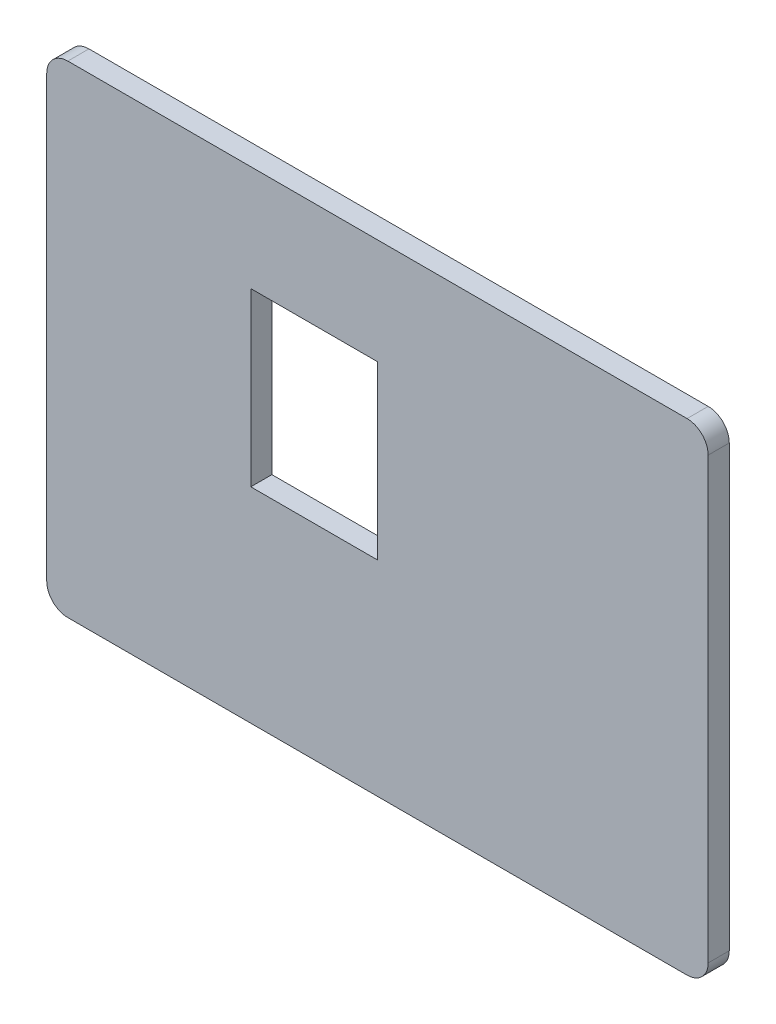
SolidWorks part; units mm, degrees
ref_plane "Alzado" through (0, 0, 0) normal (0, 0, 1) x (1, 0, 0)
ref_plane "Planta" through (0, 0, 0) normal (0, 1, 0) x (1, 0, 0)
ref_plane "Vista lateral" through (0, 0, 0) normal (1, 0, 0) x (0, 0, -1)
sketch "Croquis1" plane through (0, 0, 0) normal (0, 0, 1) x (1, 0, 0)
  line L1 (-25.0652, 6.8383) -> (21.9348, 6.8383)
  line L2 (-25.0652, 6.8383) -> (-25.0652, -27.4117)
  line L3 (-25.0652, -27.4117) -> (21.9348, -27.4117)
  line L4 (21.9348, 6.8383) -> (21.9348, -27.4117)
  dimension "D1" = 47
  dimension "D2" = 34.25
extrude "Saliente-Extruir1" add sketch "Croquis1" along normal blind 1.5
sketch "Croquis2" plane through (0, 0, 0) normal (0, 0, 1) x (1, 0, 0)
  line L0 (21.9348, 6.8383) -> (-25.0652, 6.8383) construction
  line L1 (-10.5652, -0.6617) -> (-1.5652, -0.6617)
  line L2 (-10.5652, -0.6617) -> (-10.5652, -12.8617)
  line L3 (-10.5652, -12.8617) -> (-1.5652, -12.8617)
  line L4 (-1.5652, -0.6617) -> (-1.5652, -12.8617)
  line L5 (21.9348, -27.4117) -> (21.9348, 6.8383) construction
  dimension "D1" = 7.5
  dimension "D2" = 23.5
  dimension "D3" = 9
  dimension "D4" = 12.2
extrude "Cortar-Extruir5" cut sketch "Croquis2" along normal blind 21.5
sketch "Croquis3" plane through (0, 0, 0) normal (0, 0, 1) x (1, 0, 0)
  line L0 (-25.0652, 6.8383) -> (-25.0652, -27.4117) construction
  line L1 (21.9348, 6.8383) -> (-25.0652, 6.8383) construction
  line L2 (21.9348, -27.4117) -> (21.9348, 6.8383) construction
  line L3 (-25.0652, -27.4117) -> (21.9348, -27.4117) construction
  line L4 (-25.0652, -25.9117) -> (-25.0652, -27.4117)
  line L5 (-25.0652, -27.4117) -> (-23.5652, -27.4117)
  line L6 (-25.0652, 5.3383) -> (-25.0652, 6.8383)
  line L7 (-25.0652, 6.8383) -> (-23.5652, 6.8383)
  line L8 (20.4348, 6.8383) -> (21.9348, 6.8383)
  line L9 (21.9348, 6.8383) -> (21.9348, 5.3383)
  line L10 (21.9348, -27.4117) -> (21.9348, -25.9117)
  line L11 (20.4348, -27.4117) -> (21.9348, -27.4117)
  arc A0 (-23.5652, 6.8383) -> (-25.0652, 5.3383) centre (-23.5652, 5.3383) ccw
  arc A1 (21.9348, 5.3383) -> (20.4348, 6.8383) centre (20.4348, 5.3383) ccw
  arc A2 (20.4348, -27.4117) -> (21.9348, -25.9117) centre (20.4348, -25.9117) ccw
  arc A3 (-25.0652, -25.9117) -> (-23.5652, -27.4117) centre (-23.5652, -25.9117) ccw
  dimension "D1" = 3
  dimension "D2" = 1.5
  dimension "D3" = 1.5
  dimension "D4" = 1.5
  dimension "D5" = 1.5
extrude "Cortar-Extruir6" cut sketch "Croquis3" along normal blind 21.5
